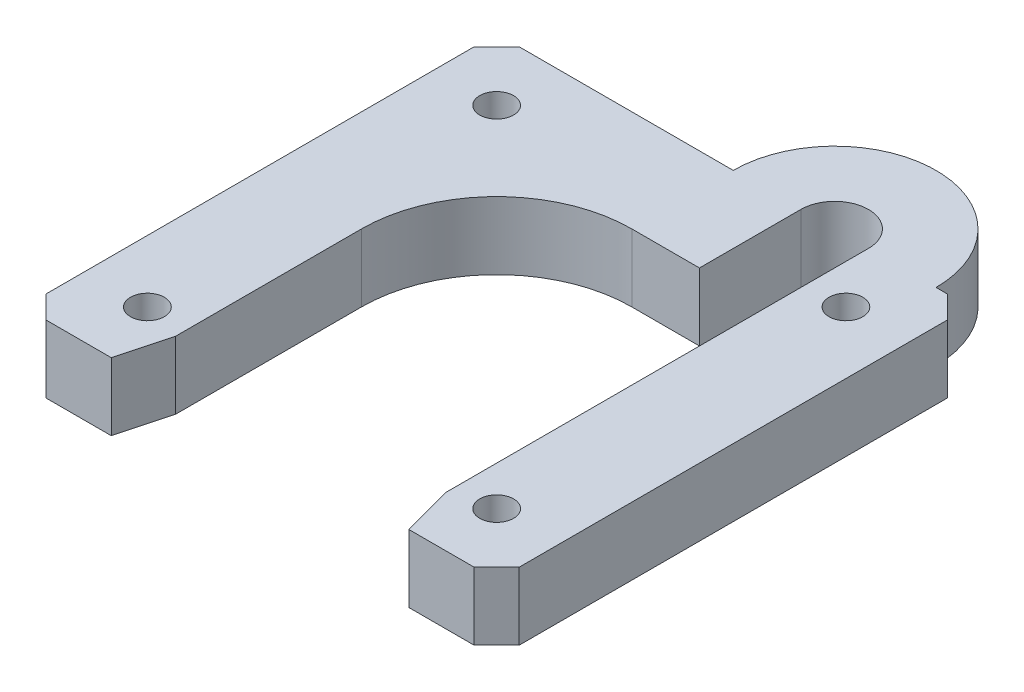
SolidWorks part; units mm, degrees
ref_plane "Front Plane" through (0, 0, 0) normal (0, 0, 1) x (1, 0, 0)
ref_plane "Top Plane" through (0, 0, 0) normal (0, 1, 0) x (1, 0, 0)
ref_plane "Right Plane" through (0, 0, 0) normal (1, 0, 0) x (0, 0, -1)
sketch "Sketch1" plane through (0, 0, 0) normal (0, 1, 0) x (1, 0, 0)
  line L1 (-21, -21) -> (21, -21)
  line L2 (-21, -21) -> (-21, 21)
  line L3 (-21, 21) -> (21, 21)
  line L4 (21, -21) -> (21, 21)
  line L5 (-21, -21) -> (21, 21) construction
  line L6 (-21, 21) -> (21, -21) construction
  line L7 (-15.5, 15.5) -> (15.5, 15.5) construction
  line L8 (-15.5, 15.5) -> (-15.5, -15.5) construction
  line L9 (-15.5, -15.5) -> (15.5, -15.5) construction
  line L10 (15.5, 15.5) -> (15.5, -15.5) construction
  circle A0 centre (0, 0) radius 12
  circle A1 centre (-15.5, 15.5) radius 1.5
  circle A2 centre (15.5, 15.5) radius 1.5
  circle A3 centre (15.5, -15.5) radius 1.5
  circle A4 centre (-15.5, -15.5) radius 1.5
  point P0 (0, 0)
  dimension "D2" = 24
  dimension "D3" = 3
  dimension "D1" = 42
  dimension "D4" = 31
extrude "Boss-Extrude1" add sketch "Sketch1" along normal blind 6
chamfer "Chamfer1" distance 2 angle 45 4 edges at (-21, 3, -21) (21, 3, -21) (21, 3, 21) (-21, 3, 21)
sketch "Sketch2" plane through (0, 6, 0) normal (0, 1, 0) x (1, 0, 0)
  line L0 (-12, 0) -> (-12, -21)
  line L1 (-19, -21) -> (19, -21) construction
  line L2 (-12, -21) -> (12, -21)
  line L3 (12, -21) -> (12, 0)
  line L4 (12, 0) -> (-12, 0)
  circle A0 centre (0, 0) radius 12 construction
extrude "Cut-Extrude1" cut sketch "Sketch2" against normal through all
chamfer "Chamfer2" distance 4.5 angle 15 2 edges at (12, 3, 21) (-12, 3, 21)
sketch "Sketch3" plane through (0, 6, 0) normal (0, 1, 0) x (1, 0, 0)
  line L0 (12, 0) -> (12, 21) construction
  line L1 (19, 21) -> (-19, 21) construction
  line L2 (6, 21) -> (6, 12) construction
  line L3 (0, 21) -> (0, 12) construction
  line L4 (0, 12) -> (6, 12) construction
  line L5 (0, 21) -> (6, 21)
  line L6 (18, 21) -> (12, 21)
  arc A0 (12, 21) -> (6, 21) centre (9, 21) ccw
  arc A1 (0, 21) -> (18, 21) centre (9, 21) cw
  arc A3 (12, 0) -> (-12, 0) centre (0, 0) ccw construction
  dimension "D1" = 6
  dimension "D2" = 3
extrude "Boss-Extrude2" add sketch "Sketch3" against normal up to surface (6 mm away) up to face at (0, 0, 4.5)
sketch "Sketch4" plane through (0, 6, 6) normal (0, 1, 0) x (1, 0, 0)
  line L0 (12, 6) -> (12, 27)
  line L2 (6, 27) -> (6, 18)
  line L3 (-3.575, 6) -> (3.575, 6) construction
  line L4 (0, 18) -> (6, 18)
  line L5 (0, 18) -> (0, 6)
  line L6 (0, 6) -> (12, 6)
  line L7 (0, 2.425) -> (0, 9.575) construction
  arc A0 (12, 27) -> (6, 27) centre (9, 27) ccw
  arc A3 (12, 27) -> (6, 27) centre (9, 27) ccw construction
  arc A4 (12, 6) -> (-12, 6) centre (0, 6) ccw construction
  dimension "D2" = 3
extrude "Cut-Extrude2" cut sketch "Sketch4" against normal through all
equation "\"M3_d\"= 3"
equation "\"housing_t\"= \"housing_t_glob@troublemaker.Assembly\""
equation "\"D3@Sketch1\"=\"M3_d\""
equation "\"D1@Boss-Extrude1\"=\"housing_t\""
